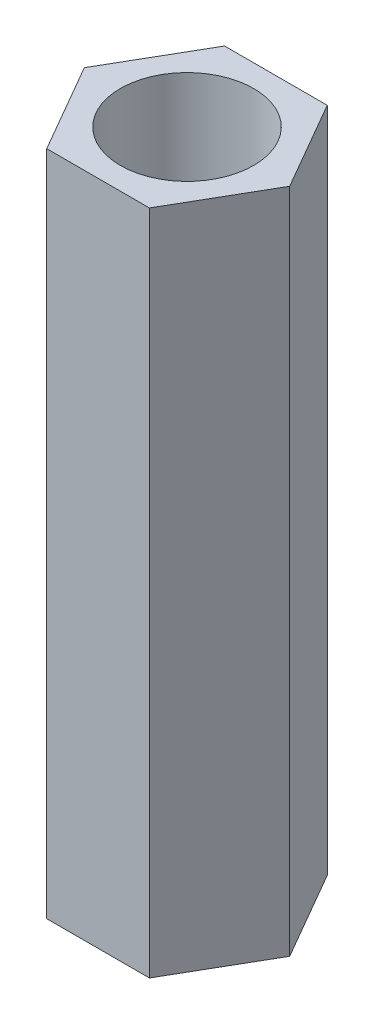
SolidWorks part; units mm, degrees
ref_plane "Front Plane" through (0, 0, 0) normal (0, 0, 1) x (1, 0, 0)
ref_plane "Top Plane" through (0, 0, 0) normal (0, 1, 0) x (1, 0, 0)
ref_plane "Right Plane" through (0, 0, 0) normal (1, 0, 0) x (0, 0, -1)
sketch "草图1" plane through (0, 0, 0) normal (0, 1, 0) x (1, 0, 0)
  line L1 (2.3094, 0) -> (1.1547, 2)
  line L2 (1.1547, 2) -> (-1.1547, 2)
  line L3 (-1.1547, 2) -> (-2.3094, 0)
  line L4 (-2.3094, 0) -> (-1.1547, -2)
  line L5 (-1.1547, -2) -> (1.1547, -2)
  line L6 (1.1547, -2) -> (2.3094, 0)
  circle A0 centre (0, 0) radius 2 construction
  dimension "D1" = 4
extrude "凸台-拉伸1" add sketch "草图1" along normal blind 15
sketch "草图2" plane through (0, 15, 0) normal (0, 1, 0) x (1, 0, 0)
  circle A0 centre (0, 0) radius 1.5
  dimension "D1" = 3
extrude "切除-拉伸1" cut sketch "草图2" against normal through all
